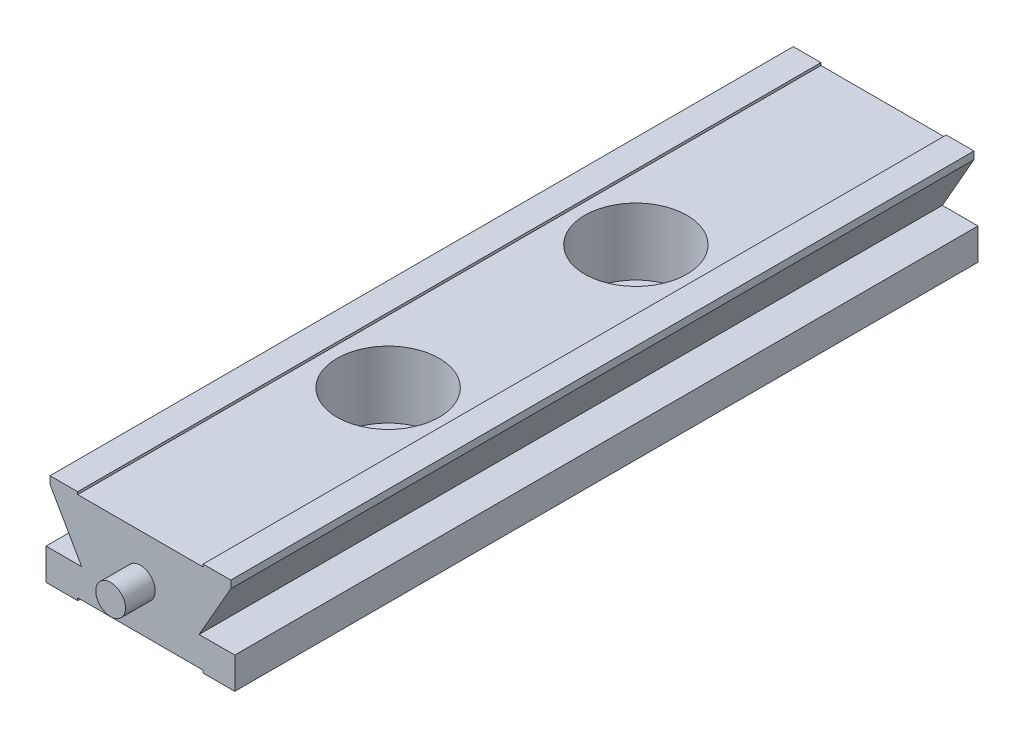
SolidWorks part; units mm, degrees
ref_plane "Front Plane" through (0, 0, 0) normal (0, 0, 1) x (1, 0, 0)
ref_plane "Top Plane" through (0, 0, 0) normal (0, 1, 0) x (1, 0, 0)
ref_plane "Right Plane" through (0, 0, 0) normal (1, 0, 0) x (0, 0, -1)
sketch "Sketch1" plane through (0, 0, 0) normal (0, 0, 1) x (1, 0, 0)
  line L0 (6.3246, 9.017) -> (6.3246, 9.271)
  line L1 (6.3246, 9.271) -> (9.1186, 9.271)
  line L2 (9.1186, 9.271) -> (9.1186, 8.509)
  line L3 (9.1186, 8.509) -> (5.9261, 2.921)
  line L4 (5.9261, 2.921) -> (9.525, 2.921)
  line L5 (9.525, 2.921) -> (9.525, -0.254)
  line L6 (9.525, -0.254) -> (6.3246, -0.254)
  line L7 (6.3246, -0.254) -> (6.3246, 0)
  line L8 (6.3246, 0) -> (-6.3246, 0)
  line L9 (-6.3246, 0) -> (-6.3246, -0.254)
  line L10 (-6.3246, -0.254) -> (-9.525, -0.254)
  line L11 (-9.525, -0.254) -> (-9.525, 2.921)
  line L12 (-9.525, 2.921) -> (-5.9261, 2.921)
  line L13 (-5.9261, 2.921) -> (-9.1186, 8.509)
  line L14 (-9.1186, 8.509) -> (-9.1186, 9.271)
  line L15 (-9.1186, 9.271) -> (-6.3246, 9.271)
  line L16 (-6.3246, 9.271) -> (-6.3246, 9.017)
  line L17 (-6.3246, 9.017) -> (6.3246, 9.017)
  line L18 (0, 0) -> (0, 11.1345) construction
  point P18 (0, 0)
  point P19 (-22.9367, -1.5075)
  point P23 (17.7104, 1.5707)
  dimension "D1" = 3.2004
  dimension "D2" = 12.6492
  dimension "D3" = 0.254
  dimension "D4" = 3.175
  dimension "D5" = 3.5989
  dimension "D6" = 11.8523
  dimension "D7" = 3.5989
  dimension "D8" = 60.26
  dimension "D9" = 60.26
  dimension "D10" = 0.762
  dimension "D11" = 2.794
  dimension "D12" = 0.762
  dimension "D13" = 0.254
extrude "Boss-Extrude1" add sketch "Sketch1" against normal blind 75
sketch "Sketch3" plane through (0, 9.017, 0) normal (0, 1, 0) x (1, 0, 0)
  line L0 (6.3246, 75) -> (-6.3246, 75) construction
  line L1 (0, 75) -> (0, -1.3236) construction
  circle A0 centre (0, 25) radius 5.155
  circle A1 centre (0, 50) radius 5.155
  point P0 (0, 0)
  point P1 (0, 75)
  point P6 (0, 25)
  point P9 (0, 50)
  dimension "D3" = 10.31
  dimension "D4" = 10.31
  dimension "D1" = 25
  dimension "D2" = 50
extrude "Cut-Extrude2" cut sketch "Sketch3" against normal blind 6.73 contours A0 | A1
sketch "Sketch4" plane through (0, 0, 0) normal (0, -1, 0) x (1, 0, 0)
  line L0 (0, -12.4014) -> (0, -87.4014) construction
  circle A0 centre (0, -25) radius 3.365
  circle A1 centre (0, -50) radius 3.365
  point P1 (0, -25)
  point P2 (0, -50)
  dimension "D3" = 6.73
  dimension "D4" = 6.73
  dimension "D1" = 25
  dimension "D2" = 50
extrude "Cut-Extrude3" cut sketch "Sketch4" against normal blind 2.54 contours A1 | A0
sketch "Sketch5" plane through (0, 0, -75) normal (0, 0, -1) x (-1, 0, 0)
  line L0 (0, 9.017) -> (0, 0) construction
  line L1 (-6.3246, 9.017) -> (6.3246, 9.017) construction
  circle A0 centre (0, 4.5085) radius 1.5
  point P5 (0, 4.5085)
  dimension "D1" = 3
extrude "Cut-Extrude4" cut sketch "Sketch5" against normal blind 3
sketch "Sketch6" plane through (0, 0, 0) normal (0, 0, 1) x (1, 0, 0)
  line L0 (0, 9.017) -> (0, 0)
  line L1 (6.3246, 9.017) -> (-6.3246, 9.017) construction
  circle A0 centre (0, 4.5085) radius 1.5
  point P5 (0, 4.5085)
  dimension "D1" = 3
extrude "Boss-Extrude2" add sketch "Sketch6" along normal blind 3 contours A0
